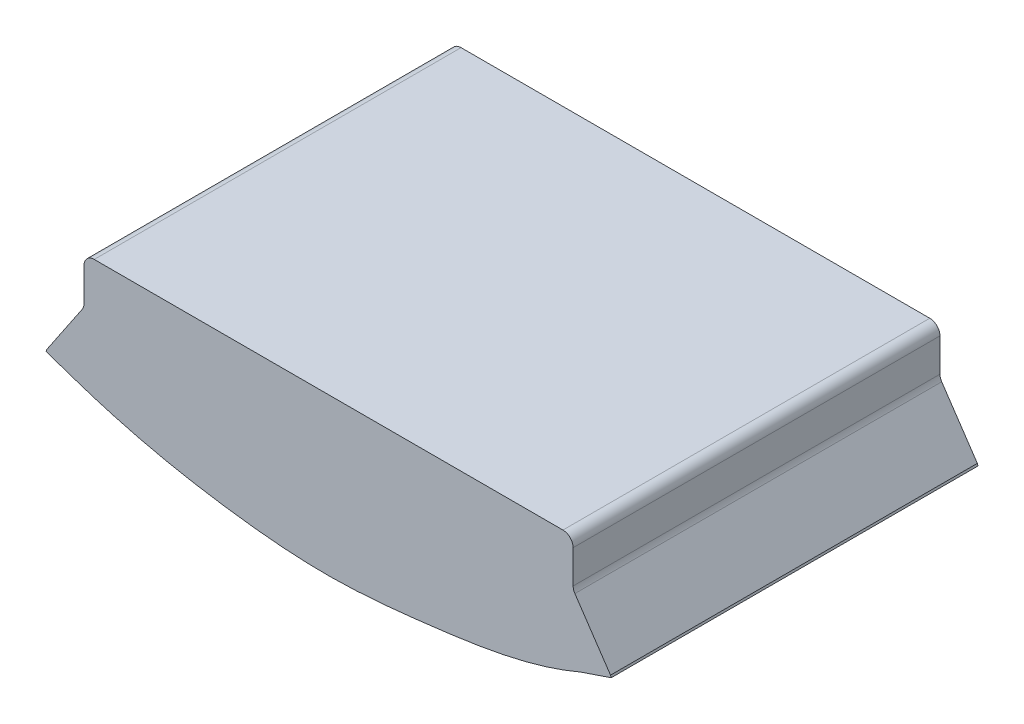
SolidWorks part; units mm, degrees
ref_plane "Front Plane" through (0, 0, 0) normal (0, 0, 1) x (1, 0, 0)
ref_plane "Top Plane" through (0, 0, 0) normal (0, 1, 0) x (1, 0, 0)
ref_plane "Right Plane" through (0, 0, 0) normal (1, 0, 0) x (0, 0, -1)
sketch "Sketch1" plane through (0, 0, 0) normal (0, 0, 1) x (1, 0, 0)
  line L0 (35.3769, -6.781) -> (36.8663, -6.2771) construction
  line L1 (9.1337, -6.2771) -> (10.6071, -6.7756) construction
  line L2 (9.1657, -6.1823) -> (10.9145, -3.5896) construction
  line L3 (35.0855, -3.5896) -> (36.8343, -6.1823) construction
  line L4 (35, -1.6823) -> (35, -3.31) construction
  line L5 (11, -3.31) -> (11, -1.6823) construction
  line L6 (11.5, -1.1823) -> (34.5, -1.1823) construction
  line L7 (35.3769, -6.781) -> (36.8663, -6.2771)
  line L8 (9.1337, -6.2771) -> (10.6071, -6.7756)
  line L9 (9.1657, -6.1823) -> (10.9145, -3.5896)
  line L10 (35.0855, -3.5896) -> (36.8343, -6.1823)
  line L11 (35, -1.6823) -> (35, -3.31)
  line L12 (11, -3.31) -> (11, -1.6823)
  line L13 (11.5, -1.1823) -> (34.5, -1.1823)
  line L14 (36.8343, -6.1823) -> (36.8663, -6.2771)
  line L15 (9.1657, -6.1823) -> (9.1337, -6.2771)
  arc A0 (10.9145, -3.5896) -> (11, -3.31) centre (10.5, -3.31) ccw construction
  arc A1 (35, -3.31) -> (35.0855, -3.5896) centre (35.5, -3.31) ccw construction
  arc A2 (35, -1.6823) -> (34.5, -1.1823) centre (34.5, -1.6823) ccw construction
  arc A3 (11.5, -1.1823) -> (11, -1.6823) centre (11.5, -1.6823) ccw construction
  arc A4 (10.9145, -3.5896) -> (11, -3.31) centre (10.5, -3.31) ccw
  arc A5 (35, -3.31) -> (35.0855, -3.5896) centre (35.5, -3.31) ccw
  arc A6 (35, -1.6823) -> (34.5, -1.1823) centre (34.5, -1.6823) ccw
  arc A7 (11.5, -1.1823) -> (11, -1.6823) centre (11.5, -1.6823) ccw
  spline S0 degree 3 poles (-2012.4061, 2208.378) (-96.8611, 148.4499) (-41.5541, 3.645) (16.1139, -8.2028) (18.1896, -8.5327) (20.5123, -8.8028) (22.5259, -8.8955) (24.1577, -8.8519) (25.3513, -8.7746) (26.6104, -8.6556) (28.0529, -8.4893) (29.7154, -8.2779) (72.6138, -1.0679) (92.8338, 105.8127) (102.7687, 2991.4709) knots -6.766601 -6.766601 -6.766601 -6.766601 0.146315 0.222399 0.304823 0.398352 0.499676 0.54457 0.593205 0.64184 0.694529 0.76476 0.840844 5.907055 5.907055 5.907055 5.907055 weights 1 1 1 1 1 1 1 1 1 1 1 1 1 1 1 only from (10.6071, -6.7756) to (35.3769, -6.781) construction
  spline S1 degree 3 poles (10.6071, -6.7756) (11.8161, -7.1847) (13.628, -7.6921) (16.1139, -8.2028) (18.1896, -8.5327) (20.5123, -8.8028) (22.5259, -8.8955) (24.1577, -8.8519) (25.3513, -8.7746) (26.6104, -8.6556) (28.0529, -8.4893) (29.7154, -8.2779) (32.2294, -7.8554) (34.1192, -7.3212) (35.3769, -6.781) knots 0 0 0 0 0.146315 0.222399 0.304823 0.398352 0.499676 0.54457 0.593205 0.64184 0.694529 0.76476 0.840844 1 1 1 1 weights 1 1 1 1 1 1 1 1 1 1 1 1 1 1 1
extrude "Boss-Extrude1" add sketch "Sketch1" against normal up to surface (18 mm away)
